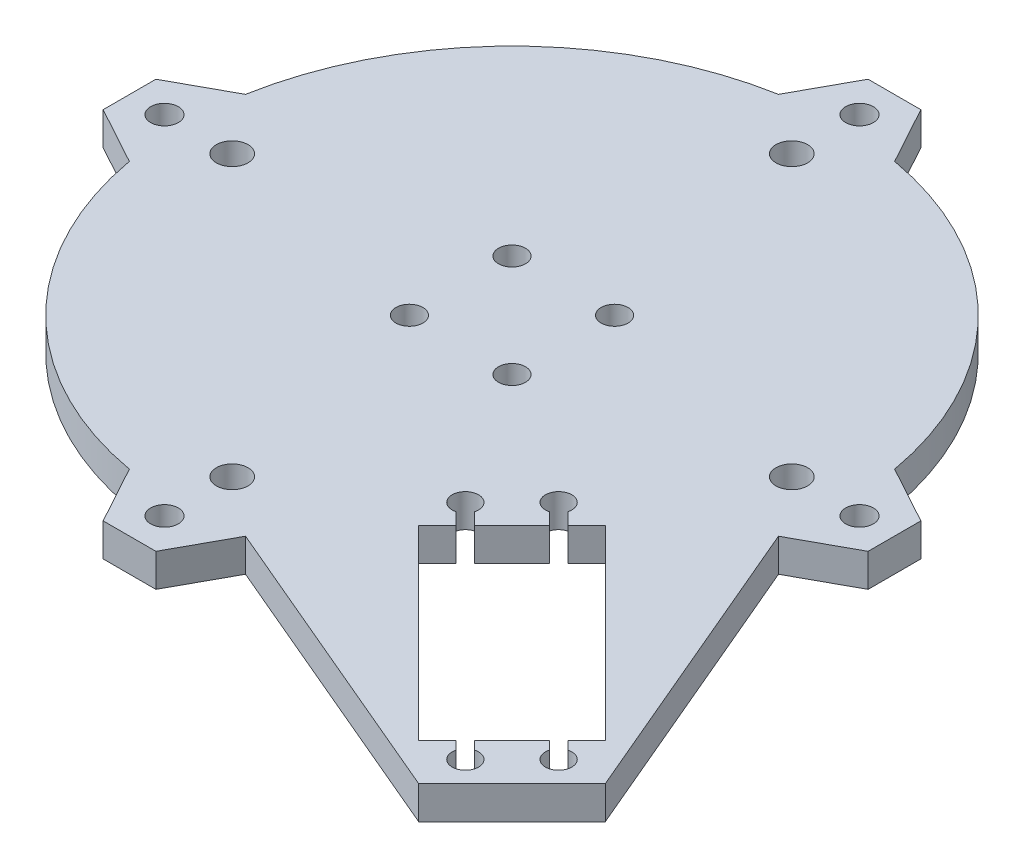
SolidWorks part; units mm, degrees
ref_plane "Alzado" through (0, 0, 0) normal (0, 0, 1) x (1, 0, 0)
ref_plane "Planta" through (0, 0, 0) normal (0, 1, 0) x (1, 0, 0)
ref_plane "Vista lateral" through (0, 0, 0) normal (1, 0, 0) x (0, 0, -1)
sketch "Croquis1" plane through (0, 0, 0) normal (0, 1, 0) x (1, 0, 0)
  line L0 (4, 58) -> (8.8071, 49.2182)
  line L1 (-4, 58) -> (4, 58)
  line L7 (-4, 58) -> (-8.8071, 49.2182)
  line L8 (58, 4) -> (58, -4)
  line L9 (58, 4) -> (49.2182, 8.8071)
  line L10 (58, -4) -> (49.2182, -8.8071)
  line L11 (4, -58) -> (-4, -58)
  line L12 (4, -58) -> (8.8071, -49.2182)
  line L13 (-4, -58) -> (-8.8071, -49.2182)
  line L14 (-58, -4) -> (-58, 4)
  line L15 (-58, -4) -> (-49.2182, -8.8071)
  line L16 (-58, 4) -> (-49.2182, 8.8071)
  arc A0 (-8.8071, 49.2182) -> (-49.2182, 8.8071) centre (0, 0) ccw
  arc A1 (-49.2182, -8.8071) -> (-8.8071, -49.2182) centre (0, 0) ccw
  arc A2 (49.2182, 8.8071) -> (8.8071, 49.2182) centre (0, 0) ccw
  arc A3 (8.8071, -49.2182) -> (49.2182, -8.8071) centre (0, 0) ccw
  point P3 (0, 50)
  point P25 (0, 0)
  dimension "D1" = 100
  dimension "D3" = 8
  dimension "D4" = 4
extrude "Saliente-Extruir1" add sketch "Croquis1" along normal blind 5
sketch "Croquis2" plane through (0, 5, 0) normal (0, 1, 0) x (1, 0, 0)
  line L0 (4, 58) -> (-4, 58) construction
  circle A0 centre (0, 52.7) radius 2.1
  circle A1 centre (52.7, 0) radius 2.1
  circle A2 centre (0, -52.7) radius 2.1
  circle A3 centre (-52.7, 0) radius 2.1
  point P13 (0, 0)
  dimension "D1" = 4.2
  dimension "D2" = 5.3
  dimension "D4" = 0
  dimension "D3" = 4
extrude "Cortar-Extruir1" cut sketch "Croquis2" against normal through all
cosmetic thread "Rosca cosmética5" parameters "D2"=5
cosmetic thread "Rosca cosmética6" parameters "D2"=5
cosmetic thread "Rosca cosmética7" parameters "D2"=5
cosmetic thread "Rosca cosmética8" parameters "D2"=5
sketch "Croquis3" plane through (0, 5, 0) normal (0, 1, 0) x (1, 0, 0)
  line L0 (0, 0) -> (33.9411, -33.9411) construction
  line L11 (20.5061, -34.6482) -> (34.6482, -20.5061)
  line L16 (20.5061, -34.6482) -> (33.234, -47.3762)
  line L23 (34.6482, -20.5061) -> (47.3762, -33.234)
  line L24 (20.5061, -34.6482) -> (47.3762, -33.234) construction
  line L25 (33.234, -47.3762) -> (34.6482, -20.5061) construction
  line L27 (33.234, -47.3762) -> (53.0768, -67.2189)
  line L28 (53.0768, -67.2189) -> (67.2189, -53.0768)
  line L29 (47.3762, -33.234) -> (67.2189, -53.0768)
  point P224 (33.9411, -56.9721)
  point P274 (21.2132, -31.2132)
  point P609 (21.2132, -48.2132)
  dimension "D1" = 18
  dimension "D2" = 20
  dimension "D3" = 48
extrude "Cortar-Extruir2" cut sketch "Croquis3" against normal through all
sketch "Croquis5" plane through (0, 5, 0) normal (0, 1, 0) x (1, 0, 0)
  line L9 (21.5541, -30.0393) -> (23.3345, -31.8198)
  line L11 (28.6251, -22.9683) -> (30.9862, -25.3293)
  line L12 (30.9862, -25.3293) -> (32.4004, -23.9151)
  line L13 (30.0393, -21.5541) -> (32.4004, -23.9151)
  line L14 (29.7686, -22.1503) -> (32.4004, -23.9151) construction
  line L15 (30.9862, -25.3293) -> (29.2214, -22.6975) construction
  line L17 (22.9683, -28.6251) -> (24.7487, -30.4056)
  line L20 (34.6482, -20.5061) -> (20.5061, -34.6482) construction
  line L21 (23.3345, -31.8198) -> (24.7487, -30.4056)
  line L22 (20.5061, -34.6482) -> (27.5699, -41.7121) construction
  line L23 (41.7121, -27.5699) -> (34.6482, -20.5061) construction
  circle A1 centre (-7.78, 7.78) radius 2.05
  circle A2 centre (7.78, 7.78) radius 2.05
  circle A3 centre (7.78, -7.78) radius 2.05
  circle A4 centre (-7.78, -7.78) radius 2.05
  arc A5 (30.0393, -21.5541) -> (28.6251, -22.9683) centre (28.1075, -21.0364) ccw
  arc A6 (22.9683, -28.6251) -> (21.5541, -30.0393) centre (21.0364, -28.1075) ccw
  point P13 (0, 0)
  dimension "D1" = 4.1
  dimension "D5" = 4
  dimension "D6" = 4
  dimension "D2" = 7.78
  dimension "D3" = 7.78
  dimension "D7" = 4.25
  dimension "D8" = 4.25
  dimension "D9" = 5
  dimension "D10" = 5
  dimension "D12" = 2
  dimension "D4" = 4
extrude "Cortar-Extruir4" cut sketch "Croquis5" against normal through all
cosmetic thread "Rosca cosmética1" parameters "D2"=5
cosmetic thread "Rosca cosmética2" parameters "D2"=5
cosmetic thread "Rosca cosmética3" parameters "D2"=5
cosmetic thread "Rosca cosmética4" parameters "D2"=5
sketch "Croquis7" plane through (0, 5, 0) normal (0, 1, 0) x (1, 0, 0)
  line L6 (68.5894, -54.4472) -> (54.4472, -68.5894)
  line L7 (48.7904, -62.9325) -> (62.9325, -48.7904)
  line L8 (68.5894, -54.4472) -> (49.2182, -8.8071)
  line L9 (34.6482, -20.5061) -> (31.8198, -23.3345) construction
  line L10 (48.7904, -62.9325) -> (27.5699, -41.7121)
  line L11 (62.9325, -48.7904) -> (41.7121, -27.5699)
  line L12 (41.7121, -27.5699) -> (46.423, -18.5717)
  line L13 (27.5699, -41.7121) -> (18.5717, -46.423)
  line L14 (49.2182, -8.8071) -> (46.423, -18.5717)
  line L15 (54.4472, -68.5894) -> (8.8071, -49.2182)
  line L16 (8.8071, -49.2182) -> (18.5717, -46.423)
  arc A0 (41.7121, -27.5699) -> (49.2182, -8.8071) centre (0, 0) ccw construction
  arc A1 (8.8071, -49.2182) -> (27.5699, -41.7121) centre (0, 0) ccw construction
  dimension "D1" = 8
  dimension "D2" = 40
extrude "Saliente-Extruir2" add sketch "Croquis7" against normal through all
sketch "Croquis8" plane through (0, 5, 0) normal (0, 1, 0) x (1, 0, 0)
  line L0 (62.9325, -48.7904) -> (48.7904, -62.9325) construction
  line L5 (54.2831, -59.94) -> (51.4902, -57.1471)
  line L6 (51.4902, -57.1471) -> (50.076, -58.5613)
  line L8 (55.8008, -67.5537) -> (55.1474, -63.8416) construction
  line L9 (55.8008, -56.19) -> (55.1474, -59.9021) construction
  line L11 (57.3718, -51.715) -> (58.7861, -50.3008)
  line L12 (57.3718, -51.715) -> (59.94, -54.2831)
  line L14 (58.7861, -50.3008) -> (61.3542, -52.8689)
  line L15 (54.4541, -59.9021) -> (53.8008, -56.19) construction
  line L18 (54.4541, -63.8416) -> (53.8008, -67.5537) construction
  line L19 (52.8689, -61.3542) -> (50.076, -58.5613)
  line L21 (62.9325, -48.7904) -> (48.7904, -62.9325) construction
  arc A3 (59.94, -54.2831) -> (61.3542, -52.8689) centre (61.8718, -54.8008) ccw
  arc A6 (52.8689, -61.3542) -> (54.2831, -59.94) centre (54.8008, -61.8718) ccw
  dimension "D1" = 4
  dimension "D3" = 3.5
  dimension "D4" = 3.5
  dimension "D7" = 2
  dimension "D8" = 2
extrude "Cortar-Extruir10" cut sketch "Croquis8" against normal through all
sketch "Croquis15" plane through (0, 0, 0) normal (0, -1, 0) x (1, 0, 0)
  line L2 (-1.1111, -20.4699) -> (-1.1111, -22.4725)
  line L4 (1.1111, -20.4699) -> (1.1111, -22.4725)
  arc A0 (1.1111, -22.4725) -> (-1.1111, -22.4725) centre (0, 0) ccw
  arc A1 (1.1111, -20.4699) -> (-1.1111, -20.4699) centre (0, 0) ccw
  point P4 (0, -19.25)
  dimension "D1" = 45
  dimension "D2" = 41
  dimension "D4" = 19.25
  dimension "D5" = 0
extrude "Saliente-Extruir4" add sketch "Croquis15" along normal blind 4
sketch "Croquis16" plane through (0, 0, 0) normal (0, -1, 0) x (1, 0, 0)
  line L0 (1.1111, -20.4699) -> (1.1111, -22.4725) construction
  line L1 (-1.1111, -20.4699) -> (-1.1111, -22.4725)
  line L2 (1.1111, -20.4699) -> (1.1111, -22.4725)
  arc A0 (-1.1111, -22.4725) -> (1.1111, -22.4725) centre (0, 0) ccw
  arc A1 (1.1111, -22.4725) -> (-1.1111, -22.4725) centre (0, 0) ccw construction
  arc A2 (-1.1111, -20.4699) -> (1.1111, -20.4699) centre (0, 0) ccw
extrude "Saliente-Extruir5" add sketch "Croquis16" along normal blind 4
sketch "Croquis17" plane through (0, 0, 0) normal (0, -1, 0) x (1, 0, 0)
  line L2 (0, 0) -> (42.43, 0) construction
  circle A2 centre (42.43, 0) radius 2.4
  circle A3 centre (0, -42.43) radius 2.4
  circle A4 centre (-42.43, 0) radius 2.4
  circle A5 centre (0, 42.43) radius 2.4
  point P13 (0, 0)
  dimension "D1" = 42.43
  dimension "D2" = 4
  dimension "D4" = 4.8
extrude "Cortar-Extruir11" cut sketch "Croquis17" against normal through all
